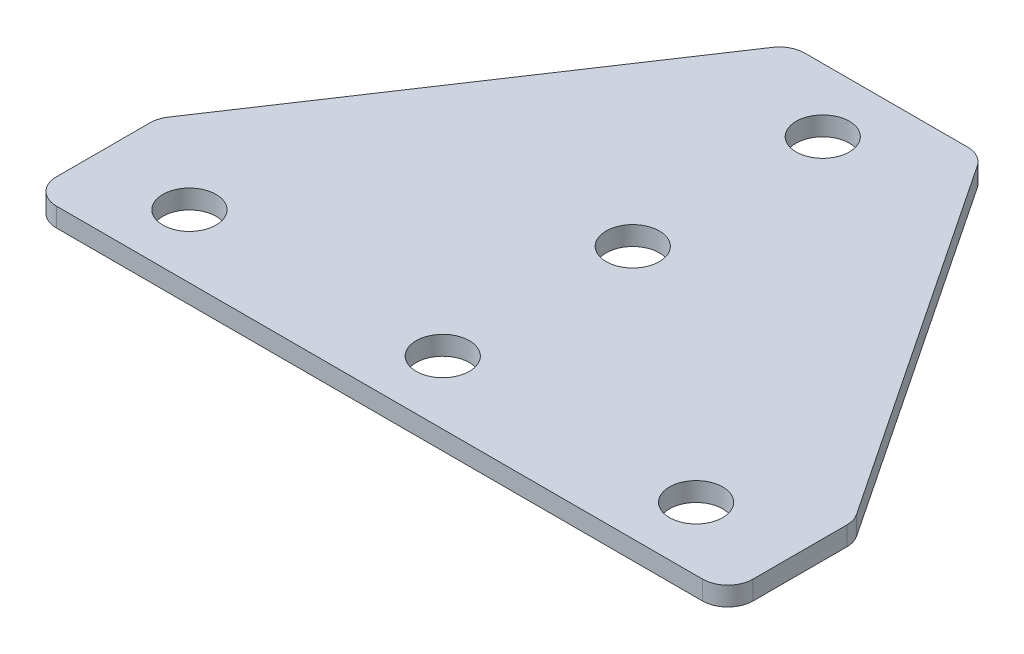
SolidWorks part; units mm, degrees
material "1060 合金"
ref_plane "正面" through (0, 0, 0) normal (0, 0, 1) x (1, 0, 0)
ref_plane "平面" through (0, 0, 0) normal (0, 1, 0) x (1, 0, 0)
ref_plane "右側面" through (0, 0, 0) normal (1, 0, 0) x (0, 0, -1)
sketch "ｽｹｯﾁ1" plane through (0, 0, 0) normal (0, 1, 0) x (1, 0, 0)
  line L0 (0, 0) -> (55, 0)
  line L1 (55, 0) -> (55, 10)
  line L2 (55, 10) -> (35, 40)
  line L3 (35, 40) -> (20, 40)
  line L4 (20, 40) -> (0, 10)
  line L5 (0, 10) -> (0, 0)
  line L6 (27.5, 0) -> (27.5, 40) construction
  line L7 (55, 5) -> (0, 5) construction
  circle A0 centre (7.5, 5) radius 2.1
  circle A1 centre (47.5, 5) radius 2.1
  circle A2 centre (27.5, 5) radius 2.1
  circle A3 centre (27.5, 35) radius 2.1
  circle A6 centre (27.5, 20) radius 2.1
  dimension "D3" = 4.2
  dimension "D4" = 7.5
  dimension "D5" = 5
  dimension "D6" = 10
  dimension "D7" = 20
  dimension "D9" = 15
  dimension "D1" = 10
  dimension "D2" = 15
extrude "ﾎﾞｽ - 押し出し1" add sketch "ｽｹｯﾁ1" along normal blind 1.5
fillet "ﾌｨﾚｯﾄ1" radius 2 6 edges at (0, 0.75, -10) (0, 0.75, 0) (55, 0.75, 0) (55, 0.75, -10) (35, 0.75, -40) (20, 0.75, -40)
